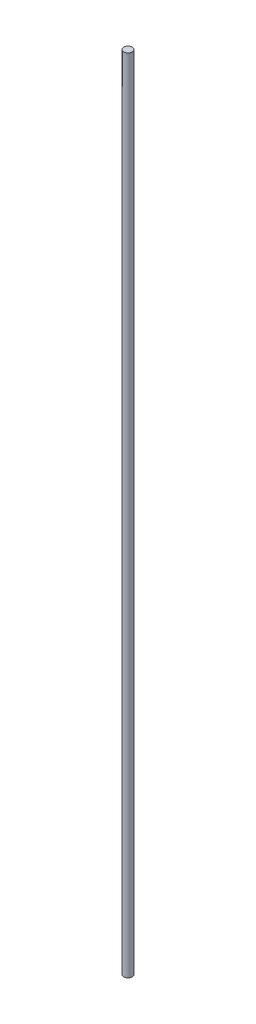
SolidWorks part; units mm, degrees
ref_plane "Front Plane" through (0, 0, 0) normal (0, 0, 1) x (1, 0, 0)
ref_plane "Top Plane" through (0, 0, 0) normal (0, 1, 0) x (1, 0, 0)
ref_plane "Right Plane" through (0, 0, 0) normal (1, 0, 0) x (0, 0, -1)
sketch "Sketch1" plane through (0, 0, 0) normal (0, 1, 0) x (1, 0, 0)
  circle A0 centre (0, 0) radius 1.5875
  dimension "D1" = 3.175
extrude "Boss-Extrude1" add sketch "Sketch1" along normal mid plane 300
